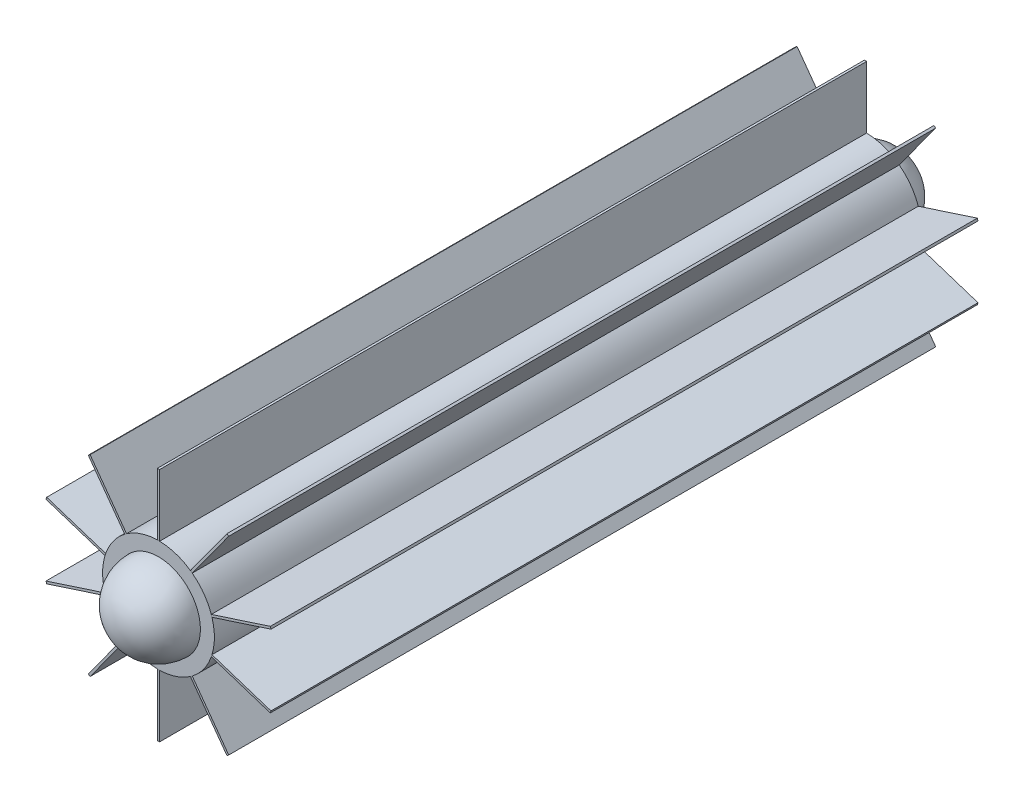
SolidWorks part; units mm, degrees
ref_plane "Front Plane" through (0, 0, 0) normal (0, 0, 1) x (1, 0, 0)
ref_plane "Top Plane" through (0, 0, 0) normal (0, 1, 0) x (1, 0, 0)
ref_plane "Right Plane" through (0, 0, 0) normal (1, 0, 0) x (0, 0, -1)
sketch "Sketch1" plane through (0, 0, 0) normal (0, 0, 1) x (1, 0, 0)
  line L0 (57.1487, 82.0611) -> (122.3991, 171.8705)
  line L1 (-2, 99.98) -> (2, 99.98)
  line L2 (-2, 99.98) -> (-2, 210.9905)
  line L3 (-2, 210.9905) -> (2, 210.9905)
  line L4 (2, 99.98) -> (2, 210.9905)
  line L5 (60.3848, 79.7099) -> (125.6352, 169.5193)
  line L6 (122.3991, 171.8705) -> (125.6352, 169.5193)
  line L7 (57.1487, 82.0611) -> (60.3848, 79.7099)
  line L8 (94.4686, 32.7976) -> (200.0459, 67.1018)
  line L9 (95.7047, 28.9934) -> (201.2819, 63.2975)
  line L10 (200.0459, 67.1018) -> (201.2819, 63.2975)
  line L11 (94.4686, 32.7976) -> (95.7047, 28.9934)
  line L12 (95.7047, -28.9934) -> (201.2819, -63.2975)
  line L13 (94.4686, -32.7976) -> (200.0459, -67.1018)
  line L14 (201.2819, -63.2975) -> (200.0459, -67.1018)
  line L15 (95.7047, -28.9934) -> (94.4686, -32.7976)
  line L16 (60.3848, -79.7099) -> (125.6352, -169.5193)
  line L17 (57.1487, -82.0611) -> (122.3991, -171.8705)
  line L18 (125.6352, -169.5193) -> (122.3991, -171.8705)
  line L19 (60.3848, -79.7099) -> (57.1487, -82.0611)
  line L20 (2, -99.98) -> (2, -210.9905)
  line L21 (-2, -99.98) -> (-2, -210.9905)
  line L22 (2, -210.9905) -> (-2, -210.9905)
  line L23 (2, -99.98) -> (-2, -99.98)
  line L24 (-57.1487, -82.0611) -> (-122.3991, -171.8705)
  line L25 (-60.3848, -79.7099) -> (-125.6352, -169.5193)
  line L26 (-122.3991, -171.8705) -> (-125.6352, -169.5193)
  line L27 (-57.1487, -82.0611) -> (-60.3848, -79.7099)
  line L28 (-94.4686, -32.7976) -> (-200.0459, -67.1018)
  line L29 (-95.7047, -28.9934) -> (-201.2819, -63.2975)
  line L30 (-200.0459, -67.1018) -> (-201.2819, -63.2975)
  line L31 (-94.4686, -32.7976) -> (-95.7047, -28.9934)
  line L32 (-95.7047, 28.9934) -> (-201.2819, 63.2975)
  line L33 (-94.4686, 32.7976) -> (-200.0459, 67.1018)
  line L34 (-201.2819, 63.2975) -> (-200.0459, 67.1018)
  line L35 (-95.7047, 28.9934) -> (-94.4686, 32.7976)
  line L36 (-60.3848, 79.7099) -> (-125.6352, 169.5193)
  line L37 (-57.1487, 82.0611) -> (-122.3991, 171.8705)
  line L38 (-125.6352, 169.5193) -> (-122.3991, 171.8705)
  line L39 (-60.3848, 79.7099) -> (-57.1487, 82.0611)
  circle A0 centre (0, 0) radius 211
  circle A1 centre (0, 0) radius 100
  dimension "D1" = 422
  dimension "D2" = 200
  dimension "D3" = 2
  dimension "D4" = 4
  dimension "D5" = 10
extrude "Boss-Extrude1" add sketch "Sketch1" along normal blind 1265 contours A1 L4 L3 L2 | A1 L37 L38 L36 | A1 L33 L34 L32 | A1 L5 L6 L0 | A1 L9 L10 L8 | A1 L13 L14 L12 | A1 L17 L18 L16 | A1 L21 L22 L20 | A1 L25 L26 L24 | A1 L29 L30 L28 | L11 A1 L7 L1 L39 L35 L31 L27 L23 L19 L15
sketch "Sketch2" plane through (0, 0, 0) normal (0, 1, 0) x (1, 0, 0)
  line L0 (0, 0) -> (0, 254.8882)
  arc A0 (65, 0) -> (0, 65) centre (0, 0) ccw
  dimension "D1" = 65
  dimension "D2" = 65
revolve "Revolve-Thin1" add sketch "Sketch2" angle 360 about L0
ref_plane "Plane1" through (0, 0, 632.5) normal (0, 0, -1) x (-1, 0, 0)
mirror "Mirror2" about plane through (0, 0, 632.5) normal (0, 0, -1) of bodies 112
